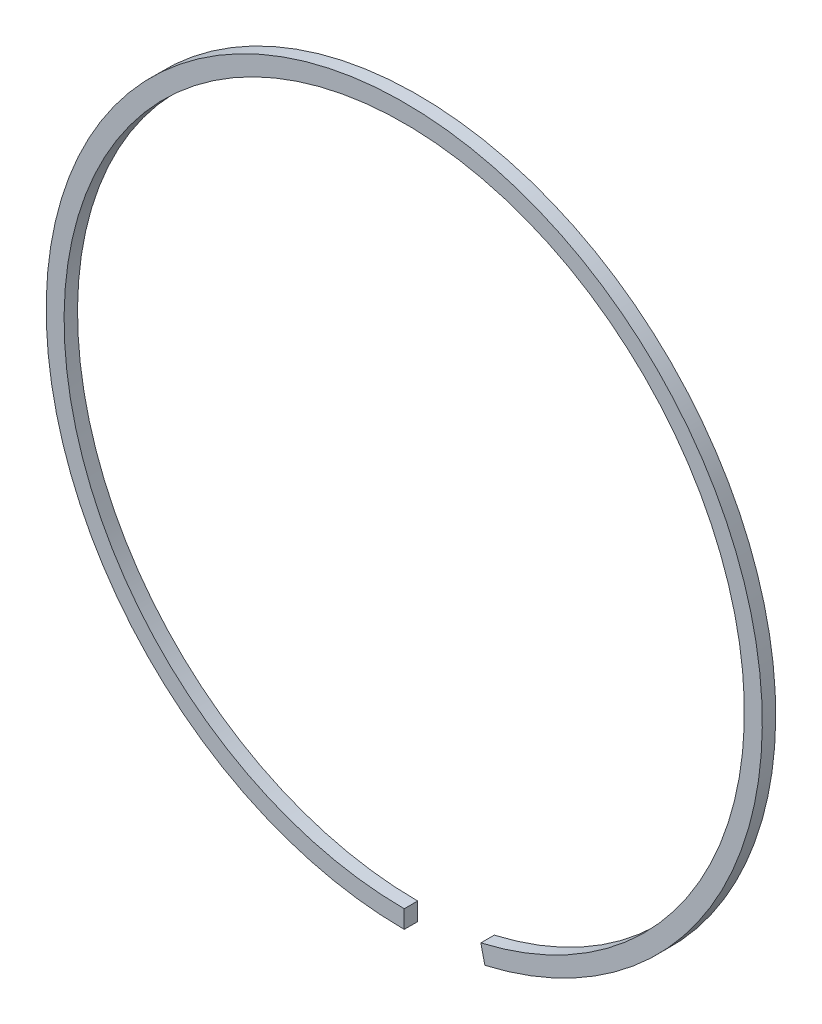
SolidWorks part; units mm, degrees
ref_plane "Alzado" through (0, 0, 0) normal (0, 0, 1) x (1, 0, 0)
ref_plane "Planta" through (0, 0, 0) normal (0, 1, 0) x (1, 0, 0)
ref_plane "Vista lateral" through (0, 0, 0) normal (1, 0, 0) x (0, 0, -1)
sketch "Croquis1" plane through (0, 0, 0) normal (0, 0, 1) x (1, 0, 0)
  line L7 (8.5562, -37.0242) -> (9.0065, -38.9729)
  line L9 (0, -38) -> (0, -40)
  arc A0 (8.5562, -37.0242) -> (0, -38) centre (0, 0) ccw
  arc A1 (9.0065, -38.9729) -> (0, -40) centre (0, 0) ccw
  dimension "D1" = 38
  dimension "D2" = 40
  dimension "D3" = 8.5562
extrude "Saliente-Extruir1" add sketch "Croquis1" along normal blind 1.5
